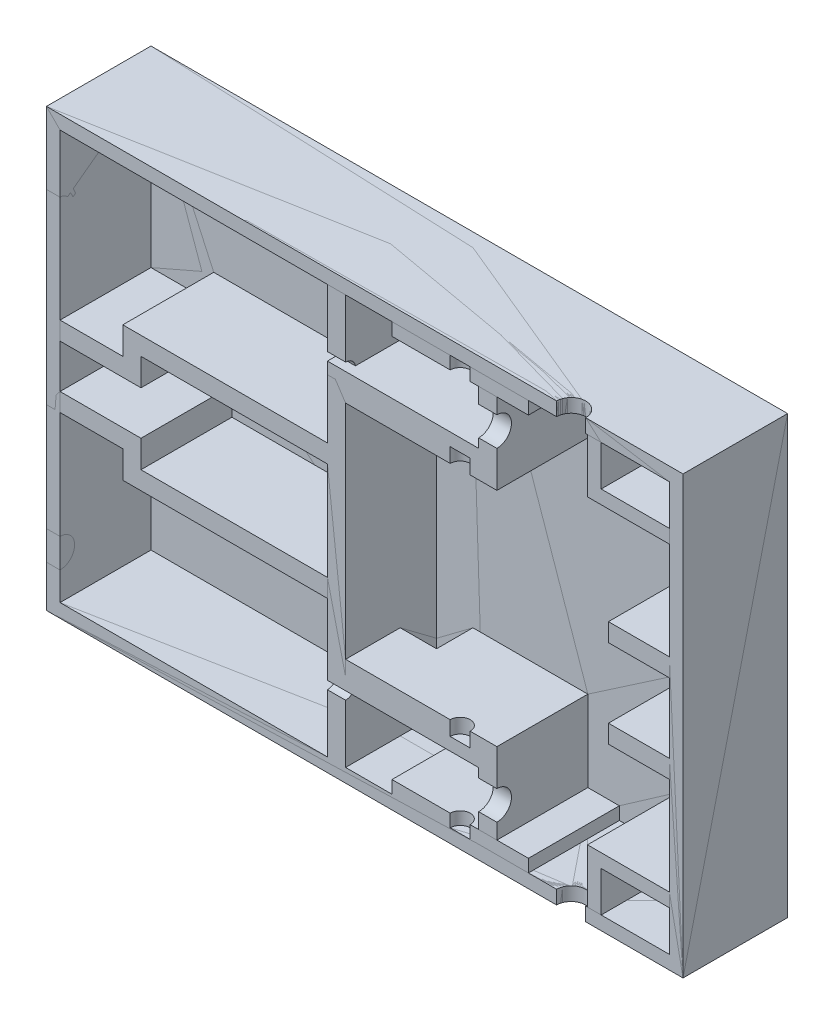
SolidWorks part; units mm, degrees
ref_plane "前视基准面" through (0, 0, 0) normal (0, 0, 1) x (1, 0, 0)
ref_plane "上视基准面" through (0, 0, 0) normal (0, 1, 0) x (1, 0, 0)
ref_plane "右视基准面" through (0, 0, 0) normal (1, 0, 0) x (0, 0, -1)
sketch "草图1" plane through (0, 0, 0) normal (0, 0, 1) x (1, 0, 0)
  line L1 (-35, 24) -> (35, 24)
  line L2 (-35, 24) -> (-35, -24)
  line L3 (-35, -24) -> (35, -24)
  line L4 (35, 24) -> (35, -24)
  line L5 (-35, 24) -> (35, -24) construction
  line L6 (-35, -24) -> (35, 24) construction
  point P0 (0, 0)
  dimension "D1" = 48
  dimension "D2" = 70
extrude "凸台-拉伸1" add sketch "草图1" along normal blind 11.5
shell "抽壳1" thickness 1.5
sketch "草图2" plane through (0, 0, 1.5) normal (0, 0, 1) x (1, 0, 0)
  line L0 (-26.6, 7.4) -> (-4.1, 7.4)
  line L1 (-33.5, 22.5) -> (-33.5, -22.5) construction
  line L9 (6.456, -12.2) -> (-2.1, -12.2)
  line L12 (12.536, -22.5) -> (12.536, -15.2)
  line L13 (12.536, -15.2) -> (8.456, -15.2)
  line L14 (-4.1, -15.2) -> (-4.1, 5.4)
  line L15 (-4.1, 5.4) -> (-24.6, 5.4)
  line L17 (-4.1, 22.5) -> (-4.1, 7.4)
  line L18 (33.5, 22.5) -> (-33.5, 22.5) construction
  line L20 (-4.1, 22.5) -> (-2.1, 22.5)
  line L21 (3, 22.5) -> (3, 21.1)
  line L22 (3, 21.1) -> (18, 21.1)
  line L23 (18, 21.1) -> (18, 22.5)
  line L24 (18, 22.5) -> (3, 22.5)
  line L25 (24.5, 22.5) -> (24.5, 16.5656)
  line L28 (-2.1, 22.5) -> (-2.1, -12.2)
  line L29 (-4.2, 12) -> (-4.2, 18) construction
  line L30 (-6.2, 7.5) -> (-26.7, 7.5) construction
  line L31 (-26.6, 7.4) -> (-26.6, 4.4)
  line L32 (-26.6, 4.4) -> (-33.5, 4.4)
  line L34 (-33.5, 2.4) -> (-24.6, 2.4)
  line L35 (-24.6, 2.4) -> (-24.6, 5.4)
  line L36 (-26.7, 4.5) -> (-32.2, 4.5) construction
  line L37 (-26.7, 4.5) -> (-26.7, 7.5) construction
  line L38 (10.5, 22.5) -> (10.5, 14.3773) construction
  line L39 (11.5, 22.5) -> (9.5, 22.5) construction
  line L41 (8.456, -15.2) -> (-4.1, -15.2)
  line L48 (24.5, 16.5656) -> (33.5, 16.5656)
  line L49 (14.536, -12.2) -> (6.456, -12.2)
  line L55 (-33.5, -22.5) -> (33.5, -22.5) construction
  line L56 (14.536, -12.2) -> (14.536, -22.5)
  line L57 (12.536, -22.5) -> (14.536, -22.5)
  line L58 (14.636, -14.05) -> (14.636, -21.55) construction
  line L60 (-33.5, 2.4) -> (-33.5, 4.4)
  line L62 (33.5, -22.5) -> (33.5, 22.5) construction
  line L63 (33.5, 16.5656) -> (33.5, 18.0656)
  line L64 (33.5, 18.0656) -> (26, 18.0656)
  line L65 (26, 18.0656) -> (26, 22.5)
  line L66 (26, 22.5) -> (24.5, 22.5)
  line L68 (13.7, 16.4656) -> (31.7, 16.4656) construction
  line L69 (26.8, -3.8344) -> (33.5, -3.8344)
  line L70 (33.5, -3.8344) -> (33.5, -5.8344)
  line L71 (33.5, -5.8344) -> (26.8, -5.8344)
  line L72 (26.8, -5.8344) -> (26.8, -3.8344)
  line L73 (27.6318, -3.7344) -> (28.796, -3.7344) construction
  dimension "D2" = 0.1
  dimension "D3" = 2
  dimension "D4" = 7.3
  dimension "D5" = 1.5
  dimension "D6" = 2
  dimension "D7" = 1.5
  dimension "D8" = 2
  dimension "D9" = 0.1
  dimension "D10" = 3
  dimension "D11" = 0.1
  dimension "D12" = 2
  dimension "D13" = 9
  dimension "D14" = 0.1
  dimension "D15" = 0.1
  dimension "D16" = 1.4
  dimension "D17" = 15
  dimension "D18" = 2
  dimension "D19" = 0.1
  dimension "D20" = 0.1
  dimension "D21" = 2
  dimension "D22" = 6.7
extrude "凸台-拉伸2" add sketch "草图2" along normal up to surface (10 mm away) up to face at (0, 0, 11.5)
sketch "草图3" plane through (0, -24, 0) normal (0, -1, 0) x (1, 0, 0)
  line L0 (-2.1, 5.5) -> (1.9, 5.5)
  line L2 (1.9, 5.5) -> (1.9, 1.5)
  line L3 (1.9, 1.5) -> (-2.1, 1.5)
  line L4 (-2.1, 1.5) -> (-2.1, 5.5)
  line L5 (-33.5, 1.5) -> (12.536, 1.5) construction
  line L6 (-2.1, 11.5) -> (-2.1, 1.5) construction
  dimension "D1" = 4
  dimension "D2" = 4
extrude "切除-拉伸1" cut sketch "草图3" against normal blind 20
sketch "草图4" plane through (0, -24, 0) normal (0, -1, 0) x (1, 0, 0)
  circle A0 centre (22.7, 11.5) radius 1.6
  circle A1 centre (22.7, 11.5) radius 1.5 construction
  dimension "D1" = 0.1
extrude "切除-拉伸2" cut sketch "草图4" against normal through all
sketch "草图5" plane through (-35, 0, 0) normal (-1, 0, 0) x (0, 0, 1)
  circle A0 centre (11.5, -17.8) radius 1.6
  circle A1 centre (11.5, -17.8) radius 1.5 construction
  circle A2 centre (11.5, 15) radius 1.1
  circle A3 centre (11.5, 15) radius 1 construction
  dimension "D1" = 0.1
  dimension "D2" = 0.1
extrude "切除-拉伸3" cut sketch "草图5" against normal up to surface (49.536 mm away) up to face at (14.536, -17.35, 6.5)
sketch "草图6" plane through (0, 24, 0) normal (0, 1, 0) x (1, 0, 0)
  circle A0 centre (10.5, -11.5) radius 1.1
  circle A1 centre (10.5, -11.5) radius 1 construction
  dimension "D1" = 0.1
extrude "切除-拉伸4" cut sketch "草图6" against normal up to surface (36.3 mm away) from surface at -1.5
sketch "草图8" plane through (-35, 0, 0) normal (-1, 0, 0) x (0, 0, 1)
  line L0 (15.5, 7.5) -> (7.5, 7.5) construction
  line L1 (11.5, 7.5) -> (4, 7.5)
  line L2 (11.5, 7.5) -> (11.5, 4.4)
  line L3 (11.5, 4.4) -> (4, 4.4)
  line L4 (4, 7.5) -> (4, 4.4)
  line L5 (0, 24) -> (0, -24) construction
  line L6 (11.5, 4.4) -> (1.5, 4.4) construction
  dimension "D1" = 4
extrude "切除-拉伸5" cut sketch "草图8" against normal up to next
mirror "镜向1" about plane through (0, 0, 0) normal (0, 1, 0) of bodies 109
